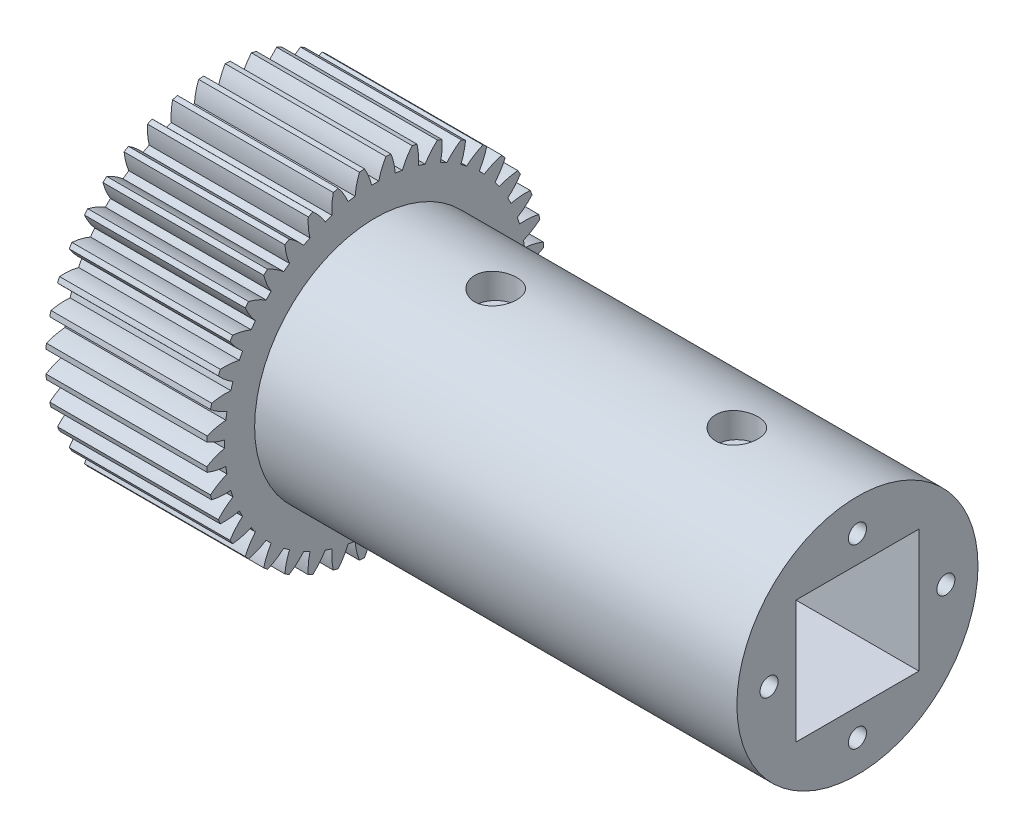
SolidWorks part; units mm, degrees
other "Markup1"
sketch "Sketch5" plane through (160, -41.9154, 41.9154) normal (0.985, -0.1562, 0.0735) x (0.1322, 0.9563, 0.2606)
ref_plane "Plane1" through (0, 0, 0) normal (0, 0, 1) x (1, 0, 0)
ref_plane "Plane2" through (0, 0, 0) normal (0, 1, 0) x (1, 0, 0)
ref_plane "Plane3" through (0, 0, 0) normal (1, 0, 0) x (0, 0, -1)
other "Configuration Table"
sketch "HoldingSke" plane through (0, 0, 0) normal (0, 1, 0) x (1, 0, 0)
  line L0 (0, 0) -> (0.383, -0.3214)
  line L1 (-15, 0) -> (100, 0) construction
  line L2 (0, 0) -> (-2.1039, 2.3779)
  line L3 (0, 0) -> (-11.863, 4.5341)
  line L4 (0, 0) -> (6.6156, 5.5511)
  line L5 (0, 0) -> (-46.8476, -17.4728)
  line L6 (0, 0) -> (-33.1585, -22.3721)
  line L7 (-2.1039, 2.3779) -> (8.6586, 51.2059)
  line L8 (-76.2, 54.61) -> (-76.1, 54.61)
  line L9 (-71.009, 38.7566) -> (-53.1078, 45.2721)
  line L10 (-76.2, 71.12) -> (104.1128, 71.12)
  line L11 (0, 0) -> (-40, 0)
  line L12 (-76.2, 101.6) -> (-76.133, 101.6)
  line L13 (24.9733, 27.94) -> (52.9518, 28.4284)
  line L14 (24.9733, 27.94) -> (24.9743, 27.94)
  line L15 (24.9733, 27.94) -> (100.4006, 29.5858)
  line L16 (-63.627, -2) -> (-12.827, -2)
  circle A0 centre (0, 0) radius 0.4
  circle A1 centre (0, 0) radius 37.499
  circle A2 centre (0, 0) radius 37.5
  circle A3 centre (0, 0) radius 0.4
  dimension "MHD" = 74.998
  dimension "Hub_dia" = 75
  dimension "Bore" = 0.8
  dimension "MBD" = 0.8
  dimension "Num_teeth" = 40
  dimension "Pitch" = 0.5
  dimension "Overall_len" = 50
  dimension "Show_teeth" = 40
  dimension "Thickness" = 40
  dimension "OAL" = 50.0001
  dimension "T_dim" = 0.1
  dimension "Ap" = 20
  dimension "H" = 19.05
  dimension "Pitch_radius" = 180.3128
  dimension "Width" = 40
  dimension "Backlash" = 0.067
  dimension "Addendum_fac" = 1
  dimension "Dedendum_fac" = 1.25
  dimension "Clearance_fac" = 0.25
  dimension "Dedendum_add" = 0.001
  dimension "Module" = 2
sketch "BasProSke" plane through (0, 0, 0) normal (0, 1, 0) x (1, 0, 0)
  line L0 (-10, 0) -> (60, 0) construction
  line L1 (0, 0) -> (0, 42)
  line L2 (0, 0) -> (40, 0)
  line L3 (40, 0) -> (40, 42)
  line L4 (40, 42) -> (0, 42)
  dimension "Thickness" = 40
  dimension "Diameter" = 84
revolve "Base-Revolve" add sketch "BasProSke" angle 360 about L0
sketch "TooCutSke" plane through (0, 0, 0) normal (1, 0, 0) x (0, 0, -1)
  line L1 (0, 0) -> (0, 107) construction
  line L2 (0, 0) -> (-1.6876, 39.9644) construction
  line L3 (0, 0) -> (-6.2726, 79.7007) construction
  line L4 (-1.6876, 39.9644) -> (-3.1363, 39.8504) construction
  arc A0 (0.8828, 37.4886) -> (-0.8828, 37.4886) centre (0, 0) ccw
  arc A1 (2.6784, 41.94) -> (-2.6784, 41.94) centre (0, 0) ccw
  circle A2 centre (0, 0) radius 40 construction
  circle A3 centre (0, 0) radius 37.5877 construction
  arc A4 (-0.8828, 37.4886) -> (-2.6784, 41.94) centre (-16.451, 33.7965) ccw
  arc A5 (2.6784, 41.94) -> (0.8828, 37.4886) centre (16.451, 33.7965) ccw
  dimension "Root_dia" = 74.998
  dimension "Overcut_dia" = 84.0508
  dimension "Pitch_dia" = 80
  dimension "Base_dia" = 75.1754
  dimension "Flank_rad" = 16
  dimension "Half_ang" = 4.5
  dimension "Half_CT" = 1.4531
extrude "ToothCut" cut sketch "TooCutSke" along normal through all
fillet "Breaks" [suppressed] radius 0.04
fillet "RootFillets" [suppressed] radius 0.501
pattern_circular "TeethCuts" count 40 every 9 about axis through (-10, 0, 0) along (1, 0, 0) of "ToothCut", "RootFillets", "Breaks"
sketch "HubNeaOneSke" plane through (0, 0, 0) normal (-1, 0, 0) x (0, 0, 1)
  circle A0 centre (0, 0) radius 37.499
  dimension "Diameter" = 74.998
extrude "HubNearOne" [suppressed] add sketch "HubNeaOneSke" along normal blind 10.0001
sketch "HubNeaBotSke" plane through (0, 0, 0) normal (-1, 0, 0) x (0, 0, 1)
  circle A0 centre (0, 0) radius 37.499
  dimension "Diameter" = 74.998
extrude "HubNearBoth" [suppressed] add sketch "HubNeaBotSke" along normal blind 5
ref_plane "FarPln" through (40, 0, 0) normal (1, 0, 0) x (0, 0, -1)
sketch "HubFarSke" plane through (40, 0, 0) normal (1, 0, 0) x (0, 0, -1)
  circle A0 centre (0, 0) radius 37.499
  dimension "Diameter" = 74.998
extrude "HubFar" [suppressed] add sketch "HubFarSke" along normal blind 5
sketch "BorSke" plane through (0, 0, 0) normal (1, 0, 0) x (0, 0, -1)
  circle A0 centre (0, 0) radius 0.4
  dimension "Diameter" = 0.8
extrude "Bore" cut sketch "BorSke" along normal mid plane 100.0001
sketch "KeySke" plane through (0, 0, 0) normal (1, 0, 0) x (0, 0, -1)
  line L0 (-0.05, 0) -> (-0.05, 0.5)
  line L1 (-0.05, 0.5) -> (0.05, 0.5)
  line L2 (0.05, 0.5) -> (0.05, 0)
  line L3 (0, 0) -> (0, 34) construction
  line L4 (-0.05, 0) -> (0.05, 0)
  dimension "Offset" = 0.5
  dimension "Width" = 0.1
extrude "Keyway" [suppressed] cut sketch "KeySke" along normal mid plane 100.0001
pattern_circular "Keyway2" [suppressed] count 2 every 90 about axis through (-10, 0, 0) along (1, 0, 0)
sketch "Sketch1" plane through (40, 0, 0) normal (1, 0, 0) x (0, 0, -1)
  line L1 (15.3, 15.3) -> (-15.3, 15.3)
  line L2 (15.3, 15.3) -> (15.3, -15.3)
  line L3 (15.3, -15.3) -> (-15.3, -15.3)
  line L4 (-15.3, 15.3) -> (-15.3, -15.3)
  line L5 (15.3, 15.3) -> (-15.3, -15.3) construction
  line L6 (15.3, -15.3) -> (-15.3, 15.3) construction
  point P0 (0, 0)
  dimension "D1" = 30.6
extrude "Cut-Extrude1" cut sketch "Sketch1" against normal through all
sketch "Sketch2" plane through (40, 0, 0) normal (1, 0, 0) x (0, 0, -1)
  line L0 (-15.3, -15.3) -> (15.3, -15.3) construction
  line L1 (15.3, -15.3) -> (15.3, 15.3) construction
  line L2 (15.3, 15.3) -> (-15.3, 15.3) construction
  line L3 (-15.3, 15.3) -> (-15.3, -15.3) construction
  line L4 (-15.3, -15.3) -> (15.3, -15.3)
  line L5 (15.3, -15.3) -> (15.3, 15.3)
  line L6 (15.3, 15.3) -> (-15.3, 15.3)
  line L7 (-15.3, 15.3) -> (-15.3, -15.3)
  circle A0 centre (0, 0) radius 30
  dimension "D1" = 60
extrude "Boss-Extrude1" add sketch "Sketch2" along normal blind 120
sketch "Sketch3" plane through (160, 0, 0) normal (1, 0, 0) x (0, 0, -1)
  line L0 (0, 0) -> (22, 0) construction
  circle A0 centre (22, 0) radius 2.25
  circle A1 centre (0, -22) radius 2.25
  circle A2 centre (-22, 0) radius 2.25
  circle A3 centre (0, 22) radius 2.25
  point P13 (0, 0)
  dimension "D2" = 4.5
  dimension "D1" = 22
  dimension "D3" = 4
extrude "Cut-Extrude2" cut sketch "Sketch3" against normal blind 10
ref_plane "Mid Plane" through (100, 0, 0) normal (1, 0, 0) x (0, 0, -1)
sketch "Sketch4" plane through (0, 0, 0) normal (0, 1, 0) x (1, 0, 0)
  line L0 (160, 0) -> (40, 0) construction
  line L1 (160, -30) -> (160, 30) construction
  line L2 (40, -30) -> (40, 30) construction
  circle A0 centre (70, 0) radius 3.2
  circle A1 centre (130, 0) radius 3.2
  point P4 (70, 0)
  point P7 (0, 0)
  point P8 (100, 0)
  point P10 (130, 0)
  dimension "D3" = 6.4
  dimension "D1" = 30
  dimension "D2" = 30
extrude "Cut-Extrude3" cut sketch "Sketch4" against normal through all both and the other way through all
ref_plane "Plane5" through (0, -30, 0) normal (0, -1, 0) x (-1, 0, 0)
sketch "Sketch6" plane through (0, -30, 0) normal (0, -1, 0) x (-1, 0, 0)
  line L1 (-123.9956, 0) -> (-126.9978, 5.2)
  line L2 (-126.9978, 5.2) -> (-133.0022, 5.2)
  line L3 (-133.0022, 5.2) -> (-136.0044, 0)
  line L4 (-136.0044, 0) -> (-133.0022, -5.2)
  line L5 (-133.0022, -5.2) -> (-126.9978, -5.2)
  line L6 (-126.9978, -5.2) -> (-123.9956, 0)
  line L7 (-76.0044, 0) -> (-73.0022, -5.2)
  line L8 (-73.0022, -5.2) -> (-66.9978, -5.2)
  line L9 (-66.9978, -5.2) -> (-63.9956, 0)
  line L10 (-63.9956, 0) -> (-66.9978, 5.2)
  line L11 (-66.9978, 5.2) -> (-73.0022, 5.2)
  line L12 (-73.0022, 5.2) -> (-76.0044, 0)
  circle A0 centre (-130, 0) radius 5.2 construction
  circle A1 centre (-70, 0) radius 5.2 construction
  dimension "D1" = 10.4
extrude "Cut-Extrude4" cut sketch "Sketch6" against normal blind 10
ref_plane "Plane6" through (0, 30, 0) normal (0, 1, 0) x (1, 0, 0)
sketch "Sketch7" plane through (0, 30, 0) normal (0, 1, 0) x (1, 0, 0)
  circle A0 centre (70, 0) radius 5.25
  circle A1 centre (130, 0) radius 5.25
  dimension "D1" = 10.5
  dimension "D2" = 10.5
extrude "Cut-Extrude5" cut sketch "Sketch7" against normal blind 6.5
equation "' \"Module@HoldingSke\" = 6.35"
equation "' \"Num_teeth@HoldingSke\" = 12"
equation "' \"Ap@HoldingSke\" =  20"
equation "' \"Ap@HoldingSke\" = 20"
equation "' \"Width@HoldingSke\" = 0.5 * 25.4"
equation "' \"Hub_dia@HoldingSke\"= 1 * 25.4"
equation "' \"Hub_dia@HoldingSke\" = 1 * 25.4"
equation "' \"Overall_len@HoldingSke\" = 1.0 * 25.4"
equation "' \"Bore@HoldingSke\" = 0.75 * 25.4"
equation "' \"T_dim@HoldingSke\" = 0.1 * 25.4"
equation "' \"Width@KeySke\" = 0.25 * 25.4"
equation "' \"Show_teeth@HoldingSke\" = 13"
equation "' \"Backlash@HoldingSke\" = 0.009 * 25.4"
equation "' \"Addendum_fac@HoldingSke\" = 1.0"
equation "' \"Dedendum_fac@HoldingSke\" = 1.25"
equation "' \"Dedendum_add@HoldingSke\" = 0.00005 * 25.4"
equation "' \"Clearance_fac@HoldingSke\" = 0.25"
equation "\"Pitch@HoldingSke\" = 1 / \"Module@HoldingSke\""
equation "\"Overcut_dia@TooCutSke\" = (\"Num_teeth@HoldingSke\" + 2 * \"Addendum_fac@HoldingSke\") / \"Pitch@HoldingSke\" + 0.002 * 25.4"
equation "\"Pitch_dia@TooCutSke\" = \"Num_teeth@HoldingSke\" / \"Pitch@HoldingSke\""
equation "\"Base_dia@TooCutSke\" = \"Num_teeth@HoldingSke\" / \"Pitch@HoldingSke\" * cos((\"Ap@HoldingSke\"  * 3.14159265 / 180))"
equation "\"Root_dia@TooCutSke\" = (\"Num_teeth@HoldingSke\" + 2) / \"Pitch@HoldingSke\" - 2 * (\"Addendum_fac@HoldingSke\" + \"Dedendum_fac@HoldingSke\") / \"Pitch@HoldingSke\" - \"Dedendum_add@HoldingSke\" * 2"
equation "\"Half_ang@TooCutSke\" = 180 / \"Num_teeth@HoldingSke\""
equation "\"Half_CT@TooCutSke\" = \"Num_teeth@HoldingSke\" / \"Pitch@HoldingSke\" * sin((3.14159265 / 2 / \"Num_teeth@HoldingSke\")) / 2 - 7 * \"Backlash@HoldingSke\" / 4"
equation "\"Flank_rad@TooCutSke\" = \"Num_teeth@HoldingSke\" / \"Pitch@HoldingSke\" / 5"
equation "\"Radius@RootFillets\" = \"Clearance_fac@HoldingSke\" / \"Pitch@HoldingSke\" + \"Dedendum_add@HoldingSke\""
equation "\"Break_rad@Breaks\" = 0.02 / \"Pitch@HoldingSke\""
equation "\"Thickness@HoldingSke\" = \"Width@HoldingSke\""
equation "\"OAL@HoldingSke\" = \"Thickness@HoldingSke\""
equation "\"MHD@HoldingSke\" = (\"Num_teeth@HoldingSke\" + 2) / \"Pitch@HoldingSke\" - 2 * (\"Addendum_fac@HoldingSke\" + \"Dedendum_fac@HoldingSke\")  / \"Pitch@HoldingSke\" - \"Dedendum_add@HoldingSke\" * 2"
equation "\"MBD@HoldingSke\" = (\"Num_teeth@HoldingSke\" + 2) / \"Pitch@HoldingSke\" - 2 * (\"Addendum_fac@HoldingSke\" + \"Dedendum_fac@HoldingSke\")  / \"Pitch@HoldingSke\" - \"Dedendum_add@HoldingSke\" * 2 - 0.002 * 25.4"
equation "\"MHD@HoldingSke\" = ((sgn( \"MHD@HoldingSke\" - \"Hub_dia@HoldingSke\" )-1)*( \"MHD@HoldingSke\" - \"Hub_dia@HoldingSke\" ))/-2+ \"Hub_dia@HoldingSke\""
equation "\"MBD@HoldingSke\" = ((sgn( \"MBD@HoldingSke\" - \"Bore@HoldingSke\" )-1)*( \"MBD@HoldingSke\" - \"Bore@HoldingSke\" ))/-2+ \"Bore@HoldingSke\""
equation "\"OAL@HoldingSke\" = ((sgn( \"OAL@HoldingSke\" - \"Overall_len@HoldingSke\" )+1)*( \"OAL@HoldingSke\" - \"Overall_len@HoldingSke\" ))/2 + \"Overall_len@HoldingSke\" + 0.000002 * 25.4"
equation "\"Num_teeth@TeethCuts\" = int( \"Show_teeth@HoldingSke\" ) + 1"
equation "\"Num_teeth@TeethCuts\" = ((sgn( \"Num_teeth@TeethCuts\" - \"Num_teeth@HoldingSke\" )-1)*( \"Num_teeth@TeethCuts\" - \"Num_teeth@HoldingSke\" ))/-2+ \"Num_teeth@HoldingSke\""
equation "\"Num_teeth@TeethCuts\" = ((sgn( \"Num_teeth@TeethCuts\" - 2.0)+1)*( \"Num_teeth@TeethCuts\" - 2.0))/2 +2.0"
equation "\"Angle@TeethCuts\" = 360.0 / \"Num_teeth@HoldingSke\""
equation "\"Diameter@BasProSke\" = (\"Num_teeth@HoldingSke\" + 2 * \"Addendum_fac@HoldingSke\") / \"Pitch@HoldingSke\""
equation "\"Thickness@BasProSke\"  = \"Thickness@HoldingSke\""
equation "' \"Fillet_rad@BasProSke\" =  \"Thickness@HoldingSke\" * 0.05"
equation "' \"Fillet_rad@BasProSke\" = \"Thickness@HoldingSke\" * 0.05"
equation "\"MHD@HoldingSke\" = ((sgn( \"MHD@HoldingSke\" - \"Root_dia@TooCutSke\" )-1)*( \"MHD@HoldingSke\" - \"Root_dia@TooCutSke\" ))/-2+ \"Root_dia@TooCutSke\""
equation "\"Diameter@HubNeaOneSke\" = \"MHD@HoldingSke\""
equation "\"Length@HubNearOne\" = \"OAL@HoldingSke\" - \"Thickness@BasProSke\""
equation "\"Diameter@HubNeaBotSke\" = \"MHD@HoldingSke\""
equation "\"Length@HubNearBoth\" = ( \"OAL@HoldingSke\" - \"Thickness@BasProSke\" ) / 2.0"
equation "\"Thickness@FarPln\" = \"Thickness@BasProSke\""
equation "\"Diameter@HubFarSke\" = \"MHD@HoldingSke\""
equation "\"Length@HubFar\" = ( \"OAL@HoldingSke\" - \"Thickness@BasProSke\" ) / 2.0"
equation "\"Diameter@BorSke\" = \"MBD@HoldingSke\""
equation "\"D1@Bore\" = \"OAL@HoldingSke\" * 2.0"
equation "\"D1@Keyway\" = \"OAL@HoldingSke\" * 2.0"
equation "\"Offset@KeySke\" = \"T_dim@HoldingSke\" + \"MBD@HoldingSke\" / 2.0"
equation "\"D2@Sketch4\"=\"D1@Sketch4\""
